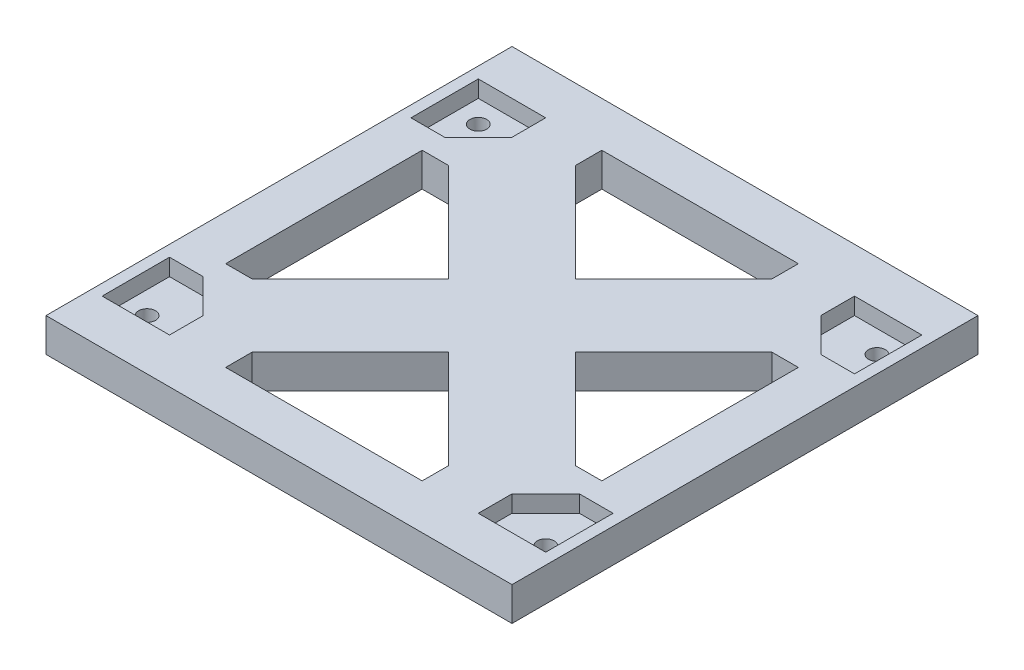
SolidWorks part; units mm, degrees
material "PVB"
ref_plane "Front Plane" through (0, 0, 0) normal (0, 0, 1) x (1, 0, 0)
ref_plane "Top Plane" through (0, 0, 0) normal (0, 1, 0) x (1, 0, 0)
ref_plane "Right Plane" through (0, 0, 0) normal (1, 0, 0) x (0, 0, -1)
sketch "Sketch1" plane through (0, 0, 0) normal (0, 1, 0) x (1, 0, 0)
  line L1 (0, 0) -> (83, 0)
  line L2 (0, 0) -> (0, 83)
  line L3 (0, 83) -> (83, 83)
  line L4 (83, 0) -> (83, 83)
  dimension "D1" = 83
  dimension "D2" = 83
extrude "Boss-Extrude1" add sketch "Sketch1" along normal blind 6
sketch "Sketch2" plane through (0, 6, 0) normal (0, 1, 0) x (1, 0, 0)
  line L0 (83, 83) -> (0, 83) construction
  line L1 (0, 83) -> (0, 0) construction
  line L2 (0, 0) -> (83, 0) construction
  line L3 (83, 0) -> (83, 83) construction
  circle A0 centre (6, 71) radius 1.5
  circle A1 centre (6, 12) radius 1.5
  circle A2 centre (77, 12) radius 1.5
  circle A3 centre (77, 71) radius 1.5
  dimension "D1" = 3
  dimension "D2" = 3
  dimension "D3" = 3
  dimension "D4" = 3
  dimension "D6" = 6
  dimension "D7" = 12
  dimension "D8" = 6
  dimension "D9" = 6
  dimension "D10" = 12
  dimension "D11" = 6
  dimension "D5" = 12
  dimension "D12" = 12
extrude "Cut-Extrude1" cut sketch "Sketch2" against normal through all
sketch "Sketch3" plane through (0, 6, 0) normal (0, 1, 0) x (1, 0, 0)
  line L0 (24, 75) -> (59, 75)
  line L1 (59, 75) -> (59, 70.3137)
  line L2 (59, 70.3137) -> (41.5, 52.8137)
  line L3 (41.5, 52.8137) -> (24, 70.3137)
  line L4 (24, 70.3137) -> (24, 75)
  line L5 (24, 70.3137) -> (59, 70.3137) construction
  line L6 (41.5, 52.8137) -> (41.5, 75) construction
  line L8 (41.5, 83) -> (41.5, 75) construction
  line L9 (83, 83) -> (0, 83) construction
  line L10 (0, 83) -> (83, 0) construction
  line L11 (0, 0) -> (83, 83) construction
  dimension "D1" = 35
  dimension "D2" = 8
  dimension "D3" = 8
extrude "Cut-Extrude2" cut sketch "Sketch3" against normal through all
ref_plane "Plane1" through (0, 0, -41.5) normal (0, 0, 1) x (1, 0, 0)
mirror "Mirror1" about plane through (0, 0, -41.5) normal (0, 0, 1) of "Cut-Extrude2"
pattern_circular "CirPattern1" count 3 every 90 about axis through (41.5, 0, -41.5) along (0, 1, 0) of "Mirror1", "Cut-Extrude2"
sketch "Sketch4" plane through (0, 6, 0) normal (0, 1, 0) x (1, 0, 0)
  line L0 (2, 20) -> (2, 8)
  line L1 (2, 8) -> (14, 8)
  line L2 (14, 14) -> (8, 20)
  line L3 (2, 20) -> (8, 20)
  line L4 (8, 20) -> (14, 14)
  line L5 (14, 14) -> (14, 8)
  line L6 (0, 83) -> (0, 0) construction
  line L7 (0, 0) -> (83, 0) construction
  circle A0 centre (6, 12) radius 1.5
  circle A1 centre (6, 12) radius 1.5 construction
  circle M21 centre (6, 12) radius 1.5
  dimension "D1" = 2
  dimension "D2" = 8
  dimension "D3" = 12
  dimension "D4" = 12
  dimension "D5" = 6
  dimension "D6" = 6
extrude "Cut-Extrude4" cut sketch "Sketch4" against normal blind 3 contours L5 L2 L3 L0 L1 M21
mirror "Mirror2" about plane through (0, 0, -41.5) normal (0, 0, 1) of "Cut-Extrude4"
ref_plane "Plane2" through (41.5, 0, 0) normal (-1, 0, 0) x (0, 0, 1)
mirror "Mirror3" about plane through (41.5, 0, 0) normal (-1, 0, 0) of "Mirror2", "Cut-Extrude4"
